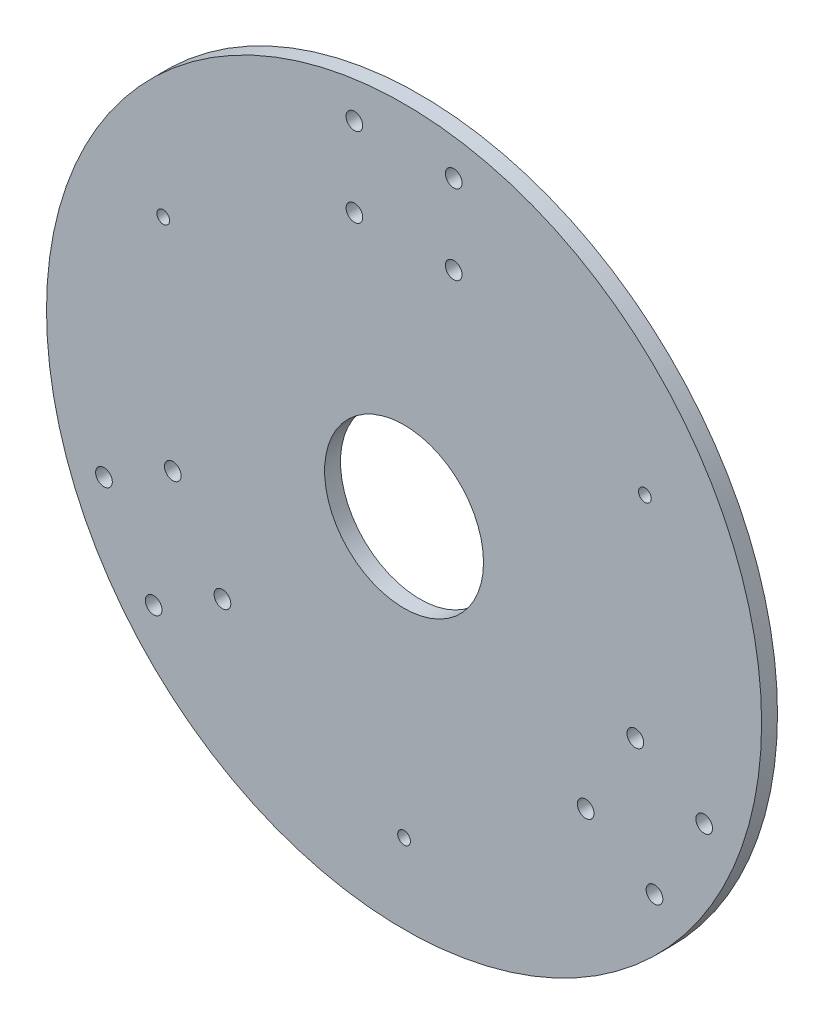
SolidWorks part; units mm, degrees
ref_plane "前视基准面" through (0, 0, 0) normal (0, 0, 1) x (1, 0, 0)
ref_plane "上视基准面" through (0, 0, 0) normal (0, 1, 0) x (1, 0, 0)
ref_plane "右视基准面" through (0, 0, 0) normal (1, 0, 0) x (0, 0, -1)
sketch "草图1" plane through (0, 0, 0) normal (0, 0, 1) x (1, 0, 0)
  line L0 (-12.5, 80) -> (12.5, 80) construction
  line L1 (17.5, 70) -> (-17.5, 70) construction
  line L2 (0, 0) -> (12.5, 60) construction
  line L6 (0, 70) -> (0, 0) construction
  circle A0 centre (12.5, 80) radius 2.1
  circle A1 centre (-12.5, 80) radius 2.1
  circle A2 centre (12.5, 60) radius 2.1
  circle A3 centre (-12.5, 60) radius 2.1
  circle A4 centre (0, 0) radius 90
  circle A5 centre (0, 0) radius 20
  circle A6 centre (75.532, -29.1747) radius 2.1
  circle A7 centre (58.2115, -19.1747) radius 2.1
  circle A8 centre (45.7115, -40.8253) radius 2.1
  circle A9 centre (63.032, -50.8253) radius 2.1
  circle A10 centre (-63.032, -50.8253) radius 2.1
  circle A11 centre (-45.7115, -40.8253) radius 2.1
  circle A12 centre (-58.2115, -19.1747) radius 2.1
  circle A13 centre (-75.532, -29.1747) radius 2.1
  point P9 (0, 70)
  dimension "D1" = 180
  dimension "D2" = 40
  dimension "D5" = 4.2
  dimension "D3" = 4.2
  dimension "D4" = 70
  dimension "D8" = 12.5
  dimension "D9" = 3
  dimension "D6" = 10
  dimension "D7" = 25
extrude "凸台-拉伸1" add sketch "草图1" along normal blind 4
sketch "草图2" plane through (0, 0, 4) normal (0, 0, 1) x (1, 0, 0)
  line L0 (-12.5, 80) -> (-12.5, 60) construction
  line L1 (-12.5, 70) -> (0, 70) construction
  circle A0 centre (0, 0) radius 70 construction
  circle A1 centre (0, -70) radius 1.6
  circle A2 centre (-60.6218, 35) radius 1.6
  circle A3 centre (60.6218, 35) radius 1.6
  point P11 (0, 0)
  point P18 (0, 0)
  dimension "D1" = 3.2
  dimension "D2" = 3
extrude "切除-拉伸1" cut sketch "草图2" against normal blind 10
